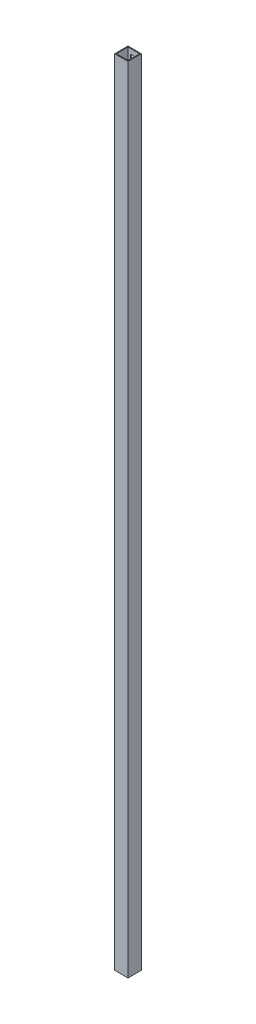
SolidWorks part; units mm, degrees
material "6061-T4 (SS)"
ref_plane "Front Plane" through (0, 0, 0) normal (0, 0, 1) x (1, 0, 0)
ref_plane "Top Plane" through (0, 0, 0) normal (0, 1, 0) x (1, 0, 0)
ref_plane "Right Plane" through (0, 0, 0) normal (1, 0, 0) x (0, 0, -1)
sketch "Sketch1" plane through (0, 0, 0) normal (0, 1, 0) x (1, 0, 0)
  line L0 (11.1125, -11.1125) -> (11.1125, 11.1125)
  line L1 (-12.7, -12.7) -> (12.7, -12.7)
  line L2 (-12.7, -12.7) -> (-12.7, 12.7)
  line L3 (-12.7, 12.7) -> (12.7, 12.7)
  line L4 (12.7, -12.7) -> (12.7, 12.7)
  line L5 (-12.7, -12.7) -> (12.7, 12.7) construction
  line L6 (-12.7, 12.7) -> (12.7, -12.7) construction
  line L7 (-11.1125, 11.1125) -> (11.1125, 11.1125)
  line L8 (-11.1125, -11.1125) -> (-11.1125, 11.1125)
  line L9 (-11.1125, -11.1125) -> (11.1125, -11.1125)
  point P0 (0, 0)
  dimension "D1" = 25.4
  dimension "D2" = 25.4
  dimension "D3" = 1.5875
extrude "Boss-Extrude1" add sketch "Sketch1" along normal blind 1511.3
sketch "Sketch3" plane through (0, 0, -12.7) normal (0, 0, -1) x (-1, 0, 0)
  line L0 (0, 1511.3) -> (0, 1445.6974) construction
  line L1 (-6.35, 1501.775) -> (6.35, 1501.775)
  line L2 (-6.35, 1501.775) -> (-6.35, 1495.425)
  line L3 (-6.35, 1495.425) -> (6.35, 1495.425)
  line L4 (6.35, 1501.775) -> (6.35, 1495.425)
  line L5 (-6.35, 1501.775) -> (6.35, 1495.425) construction
  line L6 (-6.35, 1495.425) -> (6.35, 1501.775) construction
  line L8 (-12.7, 1511.3) -> (12.7, 1511.3) construction
  point P0 (0, 1498.6)
  dimension "D1" = 12.7
  dimension "D2" = 6.35
  dimension "D3" = 12.7
extrude "Cut-Extrude1" cut sketch "Sketch3" against normal up to next
pattern_linear "LPattern1" count 59 spacing 25.4 along (0, -1, 0) of "Cut-Extrude1"
